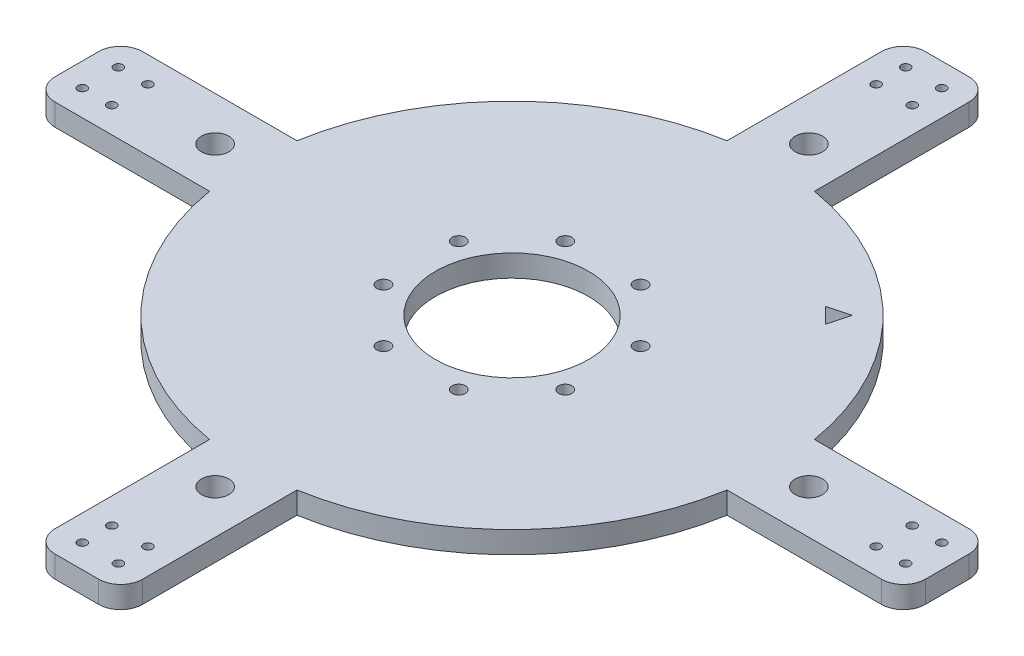
SolidWorks part; units mm, degrees
ref_plane "Front Plane" through (0, 0, 0) normal (0, 0, 1) x (1, 0, 0)
ref_plane "Top Plane" through (0, 0, 0) normal (0, 1, 0) x (1, 0, 0)
ref_plane "Right Plane" through (0, 0, 0) normal (1, 0, 0) x (0, 0, -1)
sketch "Sketch1" plane through (0, 0, 0) normal (0, 1, 0) x (1, 0, 0)
  circle A0 centre (0, 0) radius 200
  dimension "D1" = 400
extrude "Boss-Extrude1" add sketch "Sketch1" along normal blind 10
sketch "Sketch2" plane through (0, 10, 0) normal (0, 1, 0) x (1, 0, 0)
  line L0 (0, 135.7645) -> (135.7645, 0) construction
  line L1 (135.7645, 0) -> (0, -135.7645) construction
  line L2 (0, -135.7645) -> (-135.7645, 0) construction
  line L3 (-135.7645, 0) -> (0, 135.7645) construction
  line L4 (0, 0) -> (67.8823, 67.8823) construction
  line L5 (0, 0) -> (0, 55.7409) construction
  circle A0 centre (-135.7645, 0) radius 6.25
  circle A1 centre (0, -135.7645) radius 6.25
  circle A2 centre (135.7645, 0) radius 6.25
  circle A4 centre (0, 135.7645) radius 6.25
  dimension "D13" = 12.5
  dimension "D15" = 192
  dimension "D17" = 96
  dimension "D14" = 96
  dimension "D16" = 192
  dimension "D18" = 45
extrude "Cut-Extrude1" cut sketch "Sketch2" against normal through all
sketch "Sketch3" plane through (0, 10, 0) normal (0, 1, 0) x (1, 0, 0)
  circle A0 centre (0, 0) radius 35
  dimension "D1" = 70
extrude "Cut-Extrude2" cut sketch "Sketch3" against normal through all
sketch "Sketch4" plane through (0, 10, 0) normal (0, 1, 0) x (1, 0, 0)
  line L0 (0, 0) -> (0, 200) construction
  line L1 (0, 0) -> (76.5367, 184.7759) construction
  circle A0 centre (17.2208, 41.5746) radius 3.05
  circle A3 centre (0, 0) radius 200 construction
  dimension "D2" = 6.1
  dimension "D1" = 22.5
  dimension "D3" = 45
extrude "Cut-Extrude3" cut sketch "Sketch4" against normal through all
pattern_circular "CirPattern1" count 8 every 45 about axis through (0, 0, 0) along (0, 1, 0) of "Cut-Extrude3"
sketch "Sketch5" plane through (0, 10, 0) normal (0, 1, 0) x (1, 0, 0)
  line L0 (0, 0) -> (-200, 0) construction
  line L1 (-188.2645, 8.25) -> (-188.2645, -8.25) construction
  line L2 (-174.7645, 8.25) -> (-174.7645, -8.25) construction
  line L3 (-188.2645, 8.25) -> (-174.7645, 8.25) construction
  line L4 (-188.2645, -8.25) -> (-174.7645, -8.25) construction
  line L5 (-135.7645, 6.25) -> (-135.7645, -5.8775) construction
  circle A0 centre (0, 0) radius 200 construction
  circle A1 centre (-188.2645, 8.25) radius 2.05
  circle A2 centre (-174.7645, 8.25) radius 2.05
  circle A3 centre (-174.7645, -8.25) radius 2.05
  circle A4 centre (-188.2645, -8.25) radius 2.05
  circle A5 centre (-135.7645, 0) radius 6.25 construction
  dimension "D7" = 4.1
  dimension "D1" = 13.5
  dimension "D2" = 8.25
  dimension "D3" = 8.25
  dimension "D8" = 39
extrude "Cut-Extrude4" cut sketch "Sketch5" against normal through all
pattern_circular "CirPattern2" count 4 every 90 about axis through (0, 0, 0) along (0, 1, 0) of "Cut-Extrude4"
sketch "Sketch6" plane through (0, 10, 0) normal (0, 1, 0) x (1, 0, 0)
  line L0 (0, 0) -> (-200, 0) construction
  line L1 (0, 0) -> (0, 200) construction
  line L2 (-41.0025, 20) -> (-198.9975, 20)
  line L3 (-41.0025, 20) -> (-41.0025, -20)
  line L4 (-41.0025, -20) -> (-198.9975, -20)
  line L5 (-198.9975, 20) -> (-198.9975, -20)
  line L6 (-41.0025, 20) -> (-198.9975, -20) construction
  line L7 (-41.0025, -20) -> (-198.9975, 20) construction
  line L9 (-20, 41.0025) -> (20, 41.0025)
  line L10 (-20, 41.0025) -> (-20, 198.9975)
  line L11 (-20, 198.9975) -> (20, 198.9975)
  line L12 (20, 41.0025) -> (20, 198.9975)
  line L13 (-20, 41.0025) -> (20, 198.9975) construction
  line L14 (-20, 198.9975) -> (20, 41.0025) construction
  circle A0 centre (0, 0) radius 120
  circle A1 centre (0, 0) radius 200 construction
  point P3 (-120, 0)
  point P12 (0, 120)
  circle M30 centre (0, 0) radius 200
  dimension "D1" = 240
  dimension "D2" = 40
  dimension "D3" = 40
extrude "Cut-Extrude5" cut sketch "Sketch6" against normal blind 10 contours A0 L10 L2 M30 | L5 M30
pattern_circular "CirPattern3" count 4 every 90 about axis through (0, 0, 0) along (0, 1, 0) of "Cut-Extrude5"
fillet "Fillet1" radius 10 8 edges at (-198.9975, 5, -20) (-20, 5, 198.9975) (198.9975, 5, 20) (20, 5, -198.9975) (-198.9975, 5, 20) (20, 5, 198.9975) (198.9975, 5, -20) (-20, 5, -198.9975)
sketch "Sketch7" plane through (0, 10, 0) normal (0, 1, 0) x (1, 0, 0)
  line L0 (0, 0) -> (84.8528, 84.8528) construction
  line L2 (77.7817, 77.7817) -> (68.1225, 75.1936)
  line L3 (68.1225, 75.1936) -> (75.1936, 68.1225)
  line L4 (75.1936, 68.1225) -> (77.7817, 77.7817)
  arc A0 (118.3216, 20) -> (20, 118.3216) centre (0, 0) ccw construction
  circle A1 centre (73.6993, 73.6993) radius 2.8868 construction
  dimension "D1" = 10
  dimension "D2" = 10
extrude "Cut-Extrude6" cut sketch "Sketch7" against normal through all
equation "\"D14@Sketch2\"=\"D17@Sketch2\""
equation "\"D15@Sketch2\"=\"D16@Sketch2\""
equation "\"D3@Sketch5\"=\"D2@Sketch5\""
equation "\"D3@Sketch6\"=\"D2@Sketch6\""
